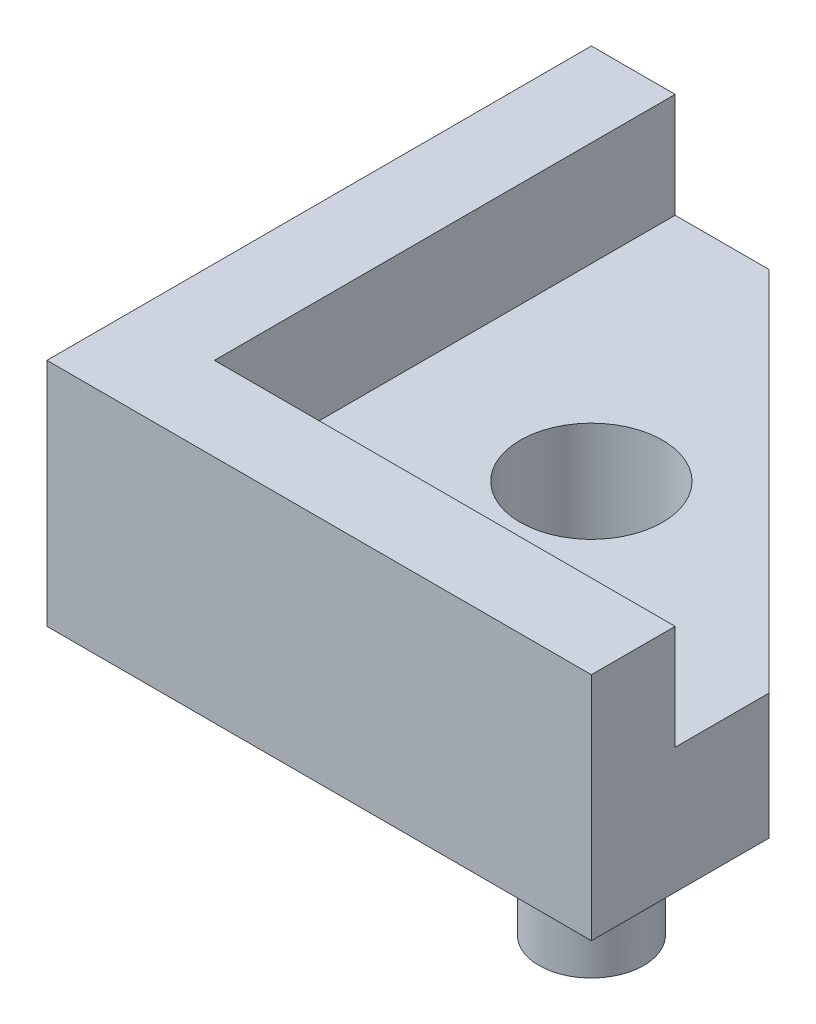
SolidWorks part; units mm, degrees
material "PET"
ref_plane "Front Plane" through (0, 0, 0) normal (0, 0, 1) x (1, 0, 0)
ref_plane "Top Plane" through (0, 0, 0) normal (0, 1, 0) x (1, 0, 0)
ref_plane "Right Plane" through (0, 0, 0) normal (1, 0, 0) x (0, 0, -1)
sketch "Board" plane through (0, 0, 0) normal (0, 1, 0) x (1, 0, 0)
  line L8 (0, 0) -> (85, 0) construction
  line L9 (0, 0) -> (0, 85) construction
  line L10 (0, 85) -> (85, 85) construction
  line L11 (85, 0) -> (85, 85) construction
  circle A1 centre (4, 4) radius 1.6 construction
  dimension "D3" = 3.2
  dimension "D1" = 85
  dimension "D2" = 85
  dimension "D4" = 4
  dimension "D5" = 4
sketch "Sketch3" plane through (0, 0, 0) normal (0, 1, 0) x (1, 0, 0)
  line L0 (-2.5, 10.5) -> (-2.5, -2.5)
  line L1 (-2.5, -2.5) -> (10.5, -2.5)
  line L2 (10.5, -2.5) -> (10.5, 1.7426)
  line L3 (10.5, 1.7426) -> (1.7426, 10.5)
  line L4 (1.7426, 10.5) -> (-2.5, 10.5)
  line L5 (0, 0) -> (0, 85) construction
  line L6 (0, 0) -> (85, 0) construction
  dimension "D1" = 2.5
  dimension "D2" = 2.5
  dimension "D3" = 45
  dimension "D4" = 13
  dimension "D5" = 13
  dimension "D6" = 3
extrude "Boss-Extrude2" add sketch "Sketch3" against normal blind 3
sketch "Sketch4" plane through (0, -3, 0) normal (0, -1, 0) x (1, 0, 0)
  line L2 (0.1109, -7.8891) -> (7.8891, -0.1109) construction
  line L3 (10.5, -1.7426) -> (1.7426, -10.5) construction
  circle A0 centre (7.8891, -0.1109) radius 1.25
  circle A1 centre (0.1109, -7.8891) radius 1.25
  dimension "D1" = 2.5
  dimension "D2" = 11
extrude "Boss-Extrude3" add sketch "Sketch4" along normal blind 2.5
sketch "Sketch5" plane through (0, 0, 0) normal (0, 1, 0) x (1, 0, 0)
  line L0 (-2.5, 10.5) -> (-2.5, -2.5)
  line L1 (-2.5, -2.5) -> (10.5, -2.5)
  line L2 (10.5, -2.5) -> (10.5, -0.5)
  line L3 (10.5, -2.5) -> (10.5, 1.7426) construction
  line L4 (10.5, -0.5) -> (-0.5, -0.5)
  line L5 (-0.5, -0.5) -> (-0.5, 10.5)
  line L7 (-0.5, 10.5) -> (-2.5, 10.5)
  line L9 (0, 0) -> (0, 85) construction
  line L10 (0, 0) -> (85, 0) construction
  dimension "D1" = 0.5
  dimension "D2" = 0.5
extrude "Boss-Extrude4" add sketch "Sketch5" along normal blind 2.5
sketch "Sketch6" plane through (0, 0, 0) normal (0, 1, 0) x (1, 0, 0)
  circle A0 centre (4, 4) radius 1.7
  dimension "D1" = 3.4
extrude "Cut-Extrude1" cut sketch "Sketch6" against normal up to next
